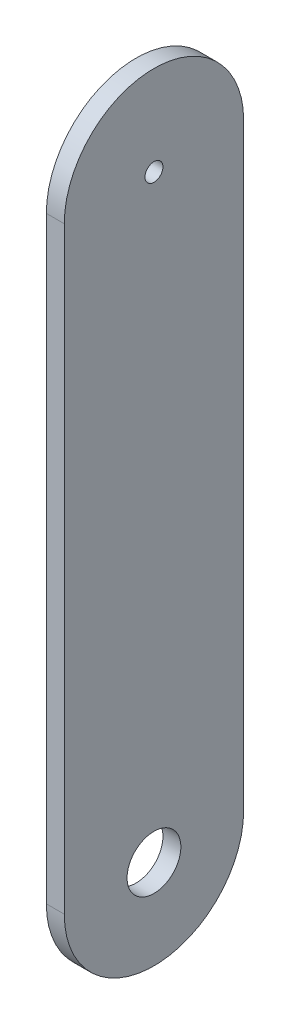
SolidWorks part; units mm, degrees
ref_plane "Front Plane" through (0, 0, 0) normal (0, 0, 1) x (1, 0, 0)
ref_plane "Top Plane" through (0, 0, 0) normal (0, 1, 0) x (1, 0, 0)
ref_plane "Right Plane" through (0, 0, 0) normal (1, 0, 0) x (0, 0, -1)
sketch "Sketch1" plane through (0, 0, 0) normal (1, 0, 0) x (0, 0, -1)
  line L0 (-5.4052, 0) -> (8.0572, 0) construction
  line L2 (0.1698, 50) -> (0.1698, -50)
  line L4 (-29.8302, 50) -> (-29.8302, -50)
  line L5 (0.168, 50.233) -> (-0.178, -53.2114) construction
  line L6 (0.1697, -49.9382) -> (-0.1809, 53.2245) construction
  arc A0 (0.1698, 50) -> (-29.8302, 50) centre (-14.8302, 50) ccw
  arc A1 (0.1698, -50) -> (-29.8302, -50) centre (-14.8302, -50) cw
  circle A2 centre (-14.8302, -50) radius 4.5
  point P0 (0, 0)
  dimension "D3" = 9
  dimension "D1" = 100
  dimension "D2" = 30
extrude "Boss-Extrude1" add sketch "Sketch1" along normal blind 3
sketch "Sketch3" plane through (3, 0, 0) normal (1, 0, 0) x (0, 0, -1)
  circle A0 centre (-14.8302, 50) radius 1.5
  dimension "D1" = 3
extrude "Cut-Extrude1" cut sketch "Sketch3" against normal blind 10
